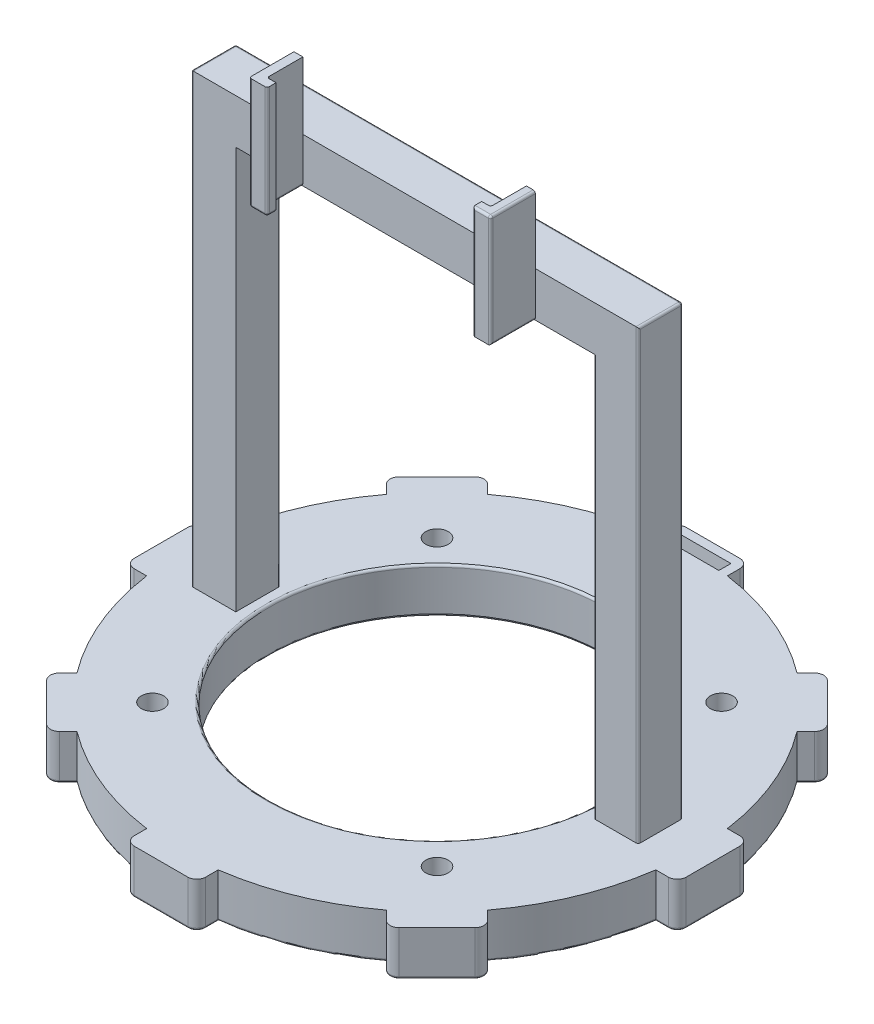
SolidWorks part; units mm, degrees
ref_plane "Front Plane" through (0, 0, 0) normal (0, 0, 1) x (1, 0, 0)
ref_plane "Top Plane" through (0, 0, 0) normal (0, 1, 0) x (1, 0, 0)
ref_plane "Right Plane" through (0, 0, 0) normal (1, 0, 0) x (0, 0, -1)
sketch "Sketch1" plane through (0, 0, 0) normal (0, 1, 0) x (1, 0, 0)
  line L0 (-8, 56.9408) -> (-8, 59.7408)
  line L1 (0, 57.5) -> (0, -57.5) construction
  line L2 (8, 56.9408) -> (8, 59.7408)
  line L3 (-6, 61.7408) -> (6, 61.7408)
  line L4 (39.4147, 47.8999) -> (47.8999, 39.4147)
  line L9 (34.6063, 45.9201) -> (36.5862, 47.8999)
  line L10 (45.9201, 34.6063) -> (47.8999, 36.5862)
  line L15 (61.7408, 6) -> (61.7408, -6)
  line L16 (56.9408, 8) -> (59.7408, 8)
  line L17 (56.9408, -8) -> (59.7408, -8)
  line L22 (47.8999, -39.4147) -> (39.4147, -47.8999)
  line L23 (45.9201, -34.6063) -> (47.8999, -36.5862)
  line L24 (34.6063, -45.9201) -> (36.5862, -47.8999)
  line L29 (6, -61.7408) -> (-6, -61.7408)
  line L30 (8, -56.9408) -> (8, -59.7408)
  line L31 (-8, -56.9408) -> (-8, -59.7408)
  line L36 (-39.4147, -47.8999) -> (-47.8999, -39.4147)
  line L37 (-34.6063, -45.9201) -> (-36.5862, -47.8999)
  line L38 (-45.9201, -34.6063) -> (-47.8999, -36.5862)
  line L43 (-61.7408, -6) -> (-61.7408, 6)
  line L44 (-56.9408, -8) -> (-59.7408, -8)
  line L45 (-56.9408, 8) -> (-59.7408, 8)
  line L50 (-47.8999, 39.4147) -> (-39.4147, 47.8999)
  line L51 (-45.9201, 34.6063) -> (-47.8999, 36.5862)
  line L52 (-34.6063, 45.9201) -> (-36.5862, 47.8999)
  arc A0 (-8, 56.9408) -> (-34.6063, 45.9201) centre (0, 0) ccw
  arc A1 (6, 61.7408) -> (8, 59.7408) centre (6, 59.7408) cw
  arc A2 (-6, 61.7408) -> (-8, 59.7408) centre (-6, 59.7408) ccw
  arc A3 (39.4147, 47.8999) -> (36.5862, 47.8999) centre (38.0005, 46.4857) ccw
  arc A4 (47.8999, 39.4147) -> (47.8999, 36.5862) centre (46.4857, 38.0005) cw
  arc A5 (61.7408, 6) -> (59.7408, 8) centre (59.7408, 6) ccw
  arc A6 (61.7408, -6) -> (59.7408, -8) centre (59.7408, -6) cw
  arc A7 (47.8999, -39.4147) -> (47.8999, -36.5862) centre (46.4857, -38.0005) ccw
  arc A8 (39.4147, -47.8999) -> (36.5862, -47.8999) centre (38.0005, -46.4857) cw
  arc A9 (6, -61.7408) -> (8, -59.7408) centre (6, -59.7408) ccw
  arc A10 (-6, -61.7408) -> (-8, -59.7408) centre (-6, -59.7408) cw
  arc A11 (-39.4147, -47.8999) -> (-36.5862, -47.8999) centre (-38.0005, -46.4857) ccw
  arc A12 (-47.8999, -39.4147) -> (-47.8999, -36.5862) centre (-46.4857, -38.0005) cw
  arc A13 (-61.7408, -6) -> (-59.7408, -8) centre (-59.7408, -6) ccw
  arc A14 (-61.7408, 6) -> (-59.7408, 8) centre (-59.7408, 6) cw
  arc A15 (-47.8999, 39.4147) -> (-47.8999, 36.5862) centre (-46.4857, 38.0005) ccw
  arc A16 (-39.4147, 47.8999) -> (-36.5862, 47.8999) centre (-38.0005, 46.4857) cw
  arc A17 (-45.9201, 34.6063) -> (-56.9408, 8) centre (0, 0) ccw
  arc A18 (-56.9408, -8) -> (-45.9201, -34.6063) centre (0, 0) ccw
  arc A19 (34.6063, 45.9201) -> (8, 56.9408) centre (0, 0) ccw
  arc A20 (-34.6063, -45.9201) -> (-8, -56.9408) centre (0, 0) ccw
  arc A21 (8, -56.9408) -> (34.6063, -45.9201) centre (0, 0) ccw
  arc A22 (45.9201, -34.6063) -> (56.9408, -8) centre (0, 0) ccw
  arc A23 (56.9408, 8) -> (45.9201, 34.6063) centre (0, 0) ccw
  point P11 (8, 61.7408)
  point P14 (-8, 61.7408)
  point P17 (-8, 58.3408)
  point P98 (0, 0)
  dimension "D1" = 115
  dimension "D2" = 2
  dimension "D3" = 16
  dimension "D4" = 2.8
  dimension "D7" = 8
extrude "Boss-Extrude1" add sketch "Sketch1" along normal blind 10
sketch "Sketch3" plane through (0, 10, 0) normal (0, 1, 0) x (1, 0, 0)
  circle A0 centre (0, 0) radius 37.6637
extrude "Cut-Extrude1" cut sketch "Sketch3" against normal through all
sketch "Sketch5" plane through (0, 10, 0) normal (0, 1, 0) x (1, 0, 0)
  line L1 (-6, 59.7408) -> (6, 59.7408)
  line L2 (-6, 59.7408) -> (-6, 57.0408)
  line L3 (-6, 57.0408) -> (6, 57.0408)
  line L4 (6, 59.7408) -> (6, 57.0408)
  line L24 (8, 56.9408) -> (8, 59.7408)
  line L25 (6, 61.7408) -> (-6, 61.7408)
  line L26 (-8, 59.7408) -> (-8, 56.9408)
  line L27 (-34.6063, 45.9201) -> (-36.5862, 47.8999)
  line L28 (-39.4147, 47.8999) -> (-47.8999, 39.4147)
  line L29 (-47.8999, 36.5862) -> (-45.9201, 34.6063)
  line L30 (-56.9408, 8) -> (-59.7408, 8)
  line L31 (-61.7408, 6) -> (-61.7408, -6)
  line L32 (-59.7408, -8) -> (-56.9408, -8)
  line L33 (-45.9201, -34.6063) -> (-47.8999, -36.5862)
  line L34 (-47.8999, -39.4147) -> (-39.4147, -47.8999)
  line L35 (-36.5862, -47.8999) -> (-34.6063, -45.9201)
  line L36 (-8, -56.9408) -> (-8, -59.7408)
  line L37 (-6, -61.7408) -> (6, -61.7408)
  line L38 (8, -59.7408) -> (8, -56.9408)
  line L39 (34.6063, -45.9201) -> (36.5862, -47.8999)
  line L40 (39.4147, -47.8999) -> (47.8999, -39.4147)
  line L41 (47.8999, -36.5862) -> (45.9201, -34.6063)
  line L42 (56.9408, -8) -> (59.7408, -8)
  line L43 (61.7408, -6) -> (61.7408, 6)
  line L44 (59.7408, 8) -> (56.9408, 8)
  line L45 (45.9201, 34.6063) -> (47.8999, 36.5862)
  line L46 (47.8999, 39.4147) -> (39.4147, 47.8999)
  line L47 (36.5862, 47.8999) -> (34.6063, 45.9201)
  line L48 (8, 56.9408) -> (8, 59.7408)
  line L49 (6, 61.7408) -> (-6, 61.7408)
  line L50 (-8, 59.7408) -> (-8, 56.9408)
  line L51 (-34.6063, 45.9201) -> (-36.5862, 47.8999)
  line L52 (-39.4147, 47.8999) -> (-47.8999, 39.4147)
  line L53 (-47.8999, 36.5862) -> (-45.9201, 34.6063)
  line L54 (-56.9408, 8) -> (-59.7408, 8)
  line L55 (-61.7408, 6) -> (-61.7408, -6)
  line L56 (-59.7408, -8) -> (-56.9408, -8)
  line L57 (-45.9201, -34.6063) -> (-47.8999, -36.5862)
  line L58 (-47.8999, -39.4147) -> (-39.4147, -47.8999)
  line L59 (-36.5862, -47.8999) -> (-34.6063, -45.9201)
  line L60 (-8, -56.9408) -> (-8, -59.7408)
  line L61 (-6, -61.7408) -> (6, -61.7408)
  line L62 (8, -59.7408) -> (8, -56.9408)
  line L63 (34.6063, -45.9201) -> (36.5862, -47.8999)
  line L64 (39.4147, -47.8999) -> (47.8999, -39.4147)
  line L65 (47.8999, -36.5862) -> (45.9201, -34.6063)
  line L66 (56.9408, -8) -> (59.7408, -8)
  line L67 (61.7408, -6) -> (61.7408, 6)
  line L68 (59.7408, 8) -> (56.9408, 8)
  line L69 (45.9201, 34.6063) -> (47.8999, 36.5862)
  line L70 (47.8999, 39.4147) -> (39.4147, 47.8999)
  line L71 (36.5862, 47.8999) -> (34.6063, 45.9201)
  arc A24 (34.6063, 45.9201) -> (8, 56.9408) centre (0, 0) ccw
  arc A25 (8, 59.7408) -> (6, 61.7408) centre (6, 59.7408) ccw
  arc A26 (-6, 61.7408) -> (-8, 59.7408) centre (-6, 59.7408) ccw
  arc A27 (-8, 56.9408) -> (-34.6063, 45.9201) centre (0, 0) ccw
  arc A28 (-36.5862, 47.8999) -> (-39.4147, 47.8999) centre (-38.0005, 46.4857) ccw
  arc A29 (-47.8999, 39.4147) -> (-47.8999, 36.5862) centre (-46.4857, 38.0005) ccw
  arc A30 (-45.9201, 34.6063) -> (-56.9408, 8) centre (0, 0) ccw
  arc A31 (-59.7408, 8) -> (-61.7408, 6) centre (-59.7408, 6) ccw
  arc A32 (-61.7408, -6) -> (-59.7408, -8) centre (-59.7408, -6) ccw
  arc A33 (-56.9408, -8) -> (-45.9201, -34.6063) centre (0, 0) ccw
  arc A34 (-47.8999, -36.5862) -> (-47.8999, -39.4147) centre (-46.4857, -38.0005) ccw
  arc A35 (-39.4147, -47.8999) -> (-36.5862, -47.8999) centre (-38.0005, -46.4857) ccw
  arc A36 (-34.6063, -45.9201) -> (-8, -56.9408) centre (0, 0) ccw
  arc A37 (-8, -59.7408) -> (-6, -61.7408) centre (-6, -59.7408) ccw
  arc A38 (6, -61.7408) -> (8, -59.7408) centre (6, -59.7408) ccw
  arc A39 (8, -56.9408) -> (34.6063, -45.9201) centre (0, 0) ccw
  arc A40 (36.5862, -47.8999) -> (39.4147, -47.8999) centre (38.0005, -46.4857) ccw
  arc A41 (47.8999, -39.4147) -> (47.8999, -36.5862) centre (46.4857, -38.0005) ccw
  arc A42 (45.9201, -34.6063) -> (56.9408, -8) centre (0, 0) ccw
  arc A43 (59.7408, -8) -> (61.7408, -6) centre (59.7408, -6) ccw
  arc A44 (61.7408, 6) -> (59.7408, 8) centre (59.7408, 6) ccw
  arc A45 (56.9408, 8) -> (45.9201, 34.6063) centre (0, 0) ccw
  arc A46 (47.8999, 36.5862) -> (47.8999, 39.4147) centre (46.4857, 38.0005) ccw
  arc A47 (39.4147, 47.8999) -> (36.5862, 47.8999) centre (38.0005, 46.4857) ccw
  arc A48 (34.6063, 45.9201) -> (8, 56.9408) centre (0, 0) ccw
  arc A49 (8, 59.7408) -> (6, 61.7408) centre (6, 59.7408) ccw
  arc A50 (-6, 61.7408) -> (-8, 59.7408) centre (-6, 59.7408) ccw
  arc A51 (-8, 56.9408) -> (-34.6063, 45.9201) centre (0, 0) ccw
  arc A52 (-36.5862, 47.8999) -> (-39.4147, 47.8999) centre (-38.0005, 46.4857) ccw
  arc A53 (-47.8999, 39.4147) -> (-47.8999, 36.5862) centre (-46.4857, 38.0005) ccw
  arc A54 (-45.9201, 34.6063) -> (-56.9408, 8) centre (0, 0) ccw
  arc A55 (-59.7408, 8) -> (-61.7408, 6) centre (-59.7408, 6) ccw
  arc A56 (-61.7408, -6) -> (-59.7408, -8) centre (-59.7408, -6) ccw
  arc A57 (-56.9408, -8) -> (-45.9201, -34.6063) centre (0, 0) ccw
  arc A58 (-47.8999, -36.5862) -> (-47.8999, -39.4147) centre (-46.4857, -38.0005) ccw
  arc A59 (-39.4147, -47.8999) -> (-36.5862, -47.8999) centre (-38.0005, -46.4857) ccw
  arc A60 (-34.6063, -45.9201) -> (-8, -56.9408) centre (0, 0) ccw
  arc A61 (-8, -59.7408) -> (-6, -61.7408) centre (-6, -59.7408) ccw
  arc A62 (6, -61.7408) -> (8, -59.7408) centre (6, -59.7408) ccw
  arc A63 (8, -56.9408) -> (34.6063, -45.9201) centre (0, 0) ccw
  arc A64 (36.5862, -47.8999) -> (39.4147, -47.8999) centre (38.0005, -46.4857) ccw
  arc A65 (47.8999, -39.4147) -> (47.8999, -36.5862) centre (46.4857, -38.0005) ccw
  arc A66 (45.9201, -34.6063) -> (56.9408, -8) centre (0, 0) ccw
  arc A67 (59.7408, -8) -> (61.7408, -6) centre (59.7408, -6) ccw
  arc A68 (61.7408, 6) -> (59.7408, 8) centre (59.7408, 6) ccw
  arc A69 (56.9408, 8) -> (45.9201, 34.6063) centre (0, 0) ccw
  arc A70 (47.8999, 36.5862) -> (47.8999, 39.4147) centre (46.4857, 38.0005) ccw
  arc A71 (39.4147, 47.8999) -> (36.5862, 47.8999) centre (38.0005, 46.4857) ccw
  dimension "D2" = 12
  dimension "D3" = 2.7
  dimension "D1" = 0
sketch "Sketch7" plane through (0, 0, 0) normal (0, -1, 0) x (1, 0, 0)
  line L0 (6, -59.7408) -> (6, -57.0408) construction
  line L1 (-6, -57.0408) -> (6, -57.0408)
  line L2 (-6, -57.0408) -> (-6, -59.3408)
  line L3 (-6, -59.3408) -> (6, -59.3408)
  line L4 (6, -57.0408) -> (6, -59.3408)
  dimension "D1" = 2.3
loft "Cut-Loft1" cut profiles "Sketch7" section "Sketch7" section "Sketch5"
sketch "Sketch14" plane through (0, 0, 0) normal (0, -1, 0) x (1, 0, 0)
  line L0 (0, 0) -> (-31.8198, 31.8198) construction
  line L1 (0, 0) -> (0, 49.5073) construction
  circle A1 centre (-31.8198, 31.8198) radius 2.5
  dimension "D1" = 45
  dimension "D2" = 5
  dimension "D3" = 45
extrude "Cut-Extrude2" cut sketch "Sketch14" against normal through all
pattern_circular "CirPattern2" count 4 over 360 about axis through (0, 0, 0) along (0, 1, 0) of "Cut-Extrude2"
sketch "Sketch16" plane through (0, 0, 0) normal (0, 0, 1) x (1, 0, 0)
  line L0 (40, 100) -> (40, 0) construction
  line L1 (45, 105) -> (45, 0) construction
  line L4 (-45, 10) -> (-45, 105) construction
  line L5 (-45, 105) -> (45, 105) construction
  line L6 (45, 105) -> (45, 10) construction
  line L7 (-40, 10) -> (-40, 100)
  line L8 (-40, 100) -> (40, 100)
  line L9 (40, 100) -> (40, 10)
  line L10 (-50, 10) -> (-50, 110)
  line L11 (-50, 110) -> (50, 110)
  line L12 (50, 110) -> (50, 10)
  line L15 (50, 10) -> (40, 10)
  line L16 (-40, 10) -> (-50, 10)
  line L17 (-50, 0) -> (-50, 110) construction
  line L18 (-40, 0) -> (-40, 100) construction
  line L19 (-45, 0) -> (-45, 105) construction
  line L20 (50, 110) -> (50, 0) construction
  dimension "D1" = 45
  dimension "D2" = 5
  dimension "D4" = 45
  dimension "D5" = 95
  dimension "D3" = 5
extrude "Boss-Extrude2" add sketch "Sketch16" along normal mid plane 10 contours L16 L7 L8 L9 L15 L12 L11 L10
sketch "Sketch17" plane through (0, 100, 0) normal (0, -1, 0) x (1, 0, 0)
  line L0 (0, 0) -> (0, 34.6332) construction
  line L6 (-40, 5) -> (40, 5) construction
  line L7 (-27, 5) -> (-25, 5)
  line L8 (-27, 5) -> (-27, 15)
  line L9 (-27, 15) -> (-25, 15)
  line L10 (-25, 5) -> (-25, 15)
  line L11 (-25, 15) -> (-23, 15)
  line L12 (-25, 15) -> (-25, 13)
  line L13 (-25, 13) -> (-23, 13)
  line L14 (-23, 15) -> (-23, 13)
  line M4 (40, 5) -> (-40, 5)
  dimension "D1" = 2
  dimension "D2" = 25
  dimension "D3" = 10
  dimension "D4" = 2
  dimension "D5" = 2
extrude "Boss-Extrude4" add sketch "Sketch17" against normal blind 25 contours L10 L9 L8 M4 | L14 L11 L10 L13
mirror "Mirror1" about plane through (0, 0, 0) normal (1, 0, 0) of "Boss-Extrude4"
fillet "Fillet4" radius 0.5 3 edges at (-25, 112.5, 13) (-23, 112.5, 15) (-27, 112.5, 15)
fillet "Fillet5" radius 0.5 77 edges at (0, 0, 37.6637) (0, 10, 37.6637) (-40, 55, -5) (0, 100, -5) (40, 55, -5) (50, 60, 5) (50, 110, 0) (-50, 60, 5) (-50, 110, 0) (40, 55, 5) (-50, 60, -5) (0, 110, -5) (50, 60, -5) (-27, 100, 9.75) (-25, 100, 8.75) (25, 100, 9) (24, 100, 13) (25, 112.5, 13) (25, 125, 15) (23, 112.5, 15) (27, 125, 10) (27, 112.5, 15) (27, 100, 10) (23, 100, 14) (-23.75, 100, 13) (-23, 100, 13.75) (-26.8536, 100, 14.8536) (-23.1464, 100, 14.8536) (-24.8536, 100, 12.8536) (35.5963, 0, -46.91) (38.0005, 0, -48.4857) (43.6573, 0, -43.6573) (48.4857, 0, -38.0005) (46.91, 0, -35.5963) (53.1231, 0, -22.0043) (58.3408, 0, -8) (61.155, 0, -7.4142) (61.7408, 0, 0) (61.155, 0, 7.4142) (58.3408, 0, 8) (53.1231, 0, 22.0043) (46.91, 0, 35.5963) (48.4857, 0, 38.0005) (43.6573, 0, 43.6573) (38.0005, 0, 48.4857) (35.5963, 0, 46.91) (22.0043, 0, 53.1231) (8, 0, 58.3408) (7.4142, 0, 61.155) (0, 0, 61.7408) (-7.4142, 0, 61.155) (-8, 0, 58.3408) (-22.0043, 0, 53.1231) (-35.5963, 0, 46.91) (-38.0005, 0, 48.4857) (-43.6573, 0, 43.6573) (-48.4857, 0, 38.0005) (-46.91, 0, 35.5963) (-53.1231, 0, 22.0043) (-58.3408, 0, 8) (-61.155, 0, 7.4142) (-61.7408, 0, 0) (-61.155, 0, -7.4142) (-58.3408, 0, -8) (-53.1231, 0, -22.0043) (-46.91, 0, -35.5963) (-48.4857, 0, -38.0005) (-43.6573, 0, -43.6573) (-38.0005, 0, -48.4857) (-35.5963, 0, -46.91) (-22.0043, 0, -53.1231) (-8, 0, -58.3408) (-7.4142, 0, -61.155) (0, 0, -61.7408) (7.4142, 0, -61.155) (8, 0, -58.3408) (22.0043, 0, -53.1231)
equation "\"85.00.00mm\"=8500"
